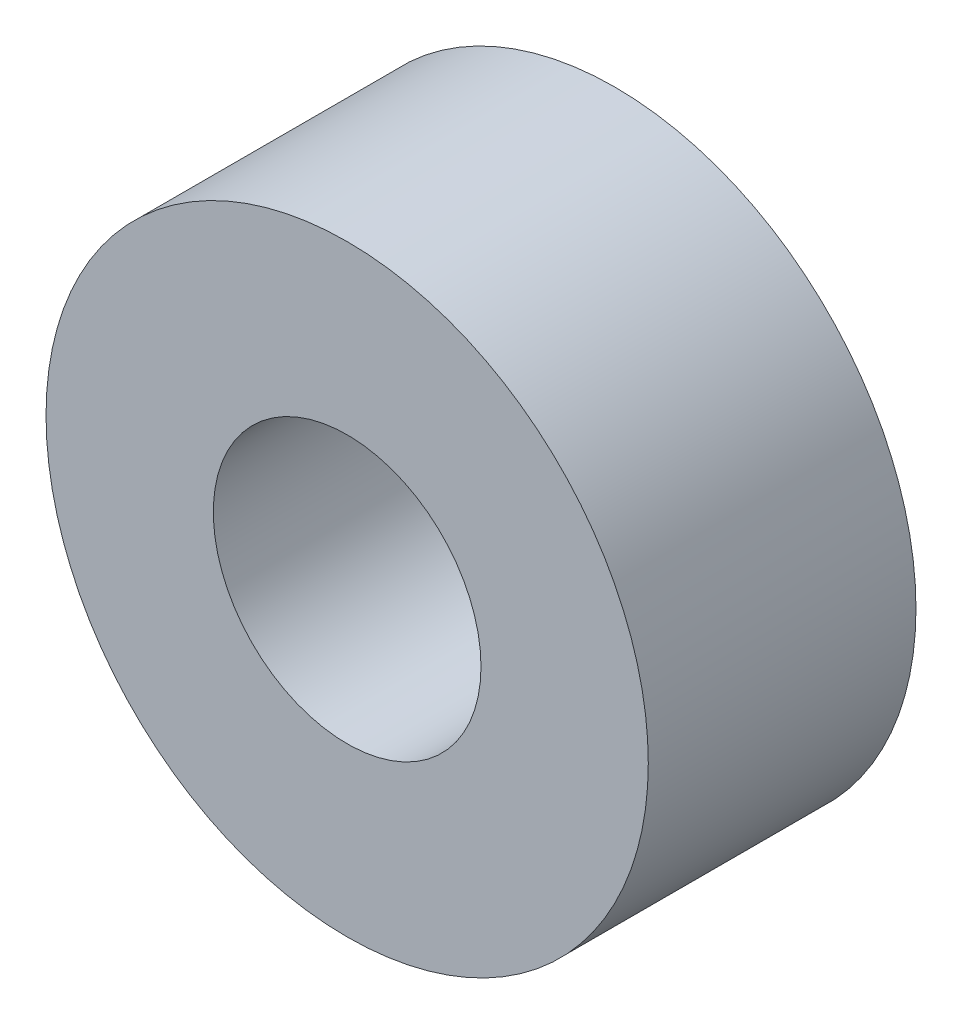
SolidWorks part; units mm, degrees
ref_plane "前视基准面" through (0, 0, 0) normal (0, 0, 1) x (1, 0, 0)
ref_plane "上视基准面" through (0, 0, 0) normal (0, 1, 0) x (1, 0, 0)
ref_plane "右视基准面" through (0, 0, 0) normal (1, 0, 0) x (0, 0, -1)
sketch "草图1" plane through (0, 0, 0) normal (0, 0, 1) x (1, 0, 0)
  circle A0 centre (0, 0) radius 4.5
  circle A1 centre (0, 0) radius 2
  dimension "D1" = 4
  dimension "D2" = 9
extrude "凸台-拉伸1" add sketch "草图1" along normal mid plane 4
